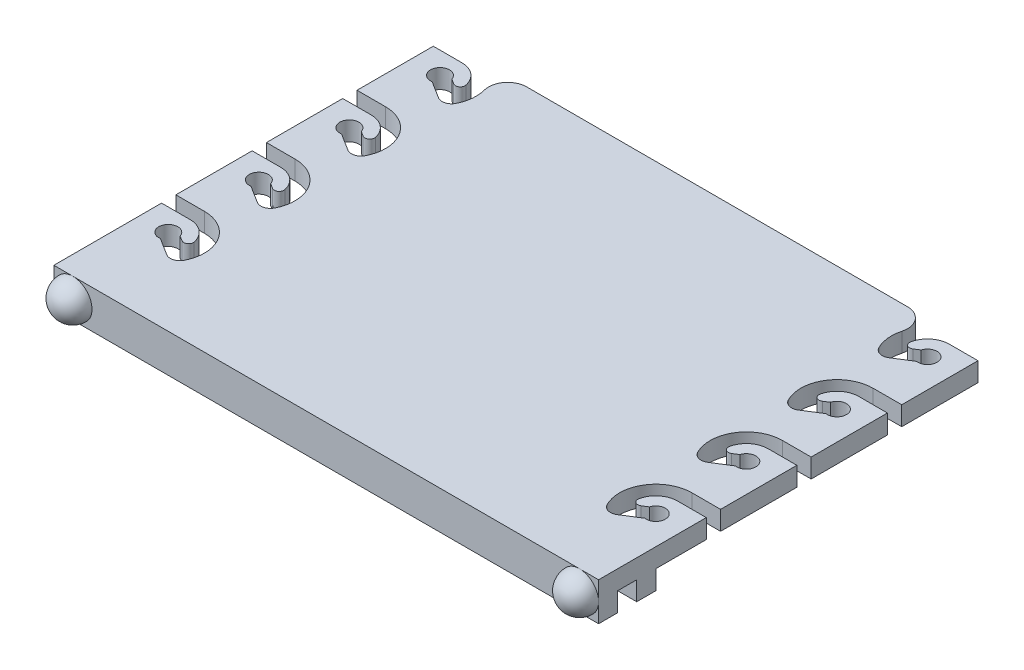
SolidWorks part; units mm, degrees
ref_plane "Front Plane" through (0, 0, 0) normal (0, 0, 1) x (1, 0, 0)
ref_plane "Top Plane" through (0, 0, 0) normal (0, 1, 0) x (1, 0, 0)
ref_plane "Right Plane" through (0, 0, 0) normal (1, 0, 0) x (0, 0, -1)
sketch "Sketch1" plane through (0, 0, 0) normal (0, 1, 0) x (1, 0, 0)
  line L0 (-28.5657, 0) -> (-28.5657, 41)
  line L1 (-28.5657, 0) -> (28.5657, 0)
  line L2 (0, 0) -> (0, 41) construction
  line L3 (-28.5657, 2) -> (-28.5657, 4) construction
  line L4 (28.5657, 0) -> (28.5657, 41)
  line L6 (-28.5657, 41) -> (28.5657, 41)
  line L7 (1.5, 41) -> (-1.5, 41) construction
extrude "Boss-Extrude1" add sketch "Sketch1" along normal blind 2
sketch "Sketch2" plane through (0, 0, 0) normal (0, -1, 0) x (1, 0, 0)
  line L0 (-28.5657, 0) -> (28.5657, 0) construction
  line L1 (-28.5657, 0) -> (28.5657, 0)
  line L2 (-28.5657, -2) -> (28.5657, -2)
  line L3 (28.5657, -2) -> (28.5657, -4)
  line L4 (28.5657, -4) -> (1.5, -4)
  line L5 (1.5, -4) -> (1.5, -20)
  line L8 (-28.5657, -2) -> (-28.5657, -4)
  line L9 (-28.5657, -4) -> (-1.5, -4)
  line L10 (-1.5, -4) -> (-1.5, -20)
  line L12 (0, -41) -> (0, 0) construction
  line L13 (-1.5, -20) -> (-3.5, -20)
  line L14 (-3.5, -20) -> (-3.5, -6)
  line L15 (-3.5, -6) -> (-28.5657, -6)
  line L16 (-28.5657, -6) -> (-28.5657, -4)
  line L17 (28.5657, -6) -> (28.5657, -4)
  line L18 (3.5, -6) -> (28.5657, -6)
  line L19 (1.5, -20) -> (3.5, -20)
  line L20 (3.5, -20) -> (3.5, -6)
  line L21 (-28.5657, -2) -> (-28.5657, 0)
  line L22 (-28.5657, 0) -> (28.5657, 0)
  line L23 (28.5657, 0) -> (28.5657, -2)
  dimension "D1" = 2
  dimension "D2" = 2
  dimension "D3" = 16
extrude "Boss-Extrude2" add sketch "Sketch2" along normal blind 2 contours L2 L12 L22 L21 | L12 L2 L23 L1 | L19 L20 L18 L17 L4 L5 | L16 L15 L14 L13 L10 L9
sketch "Sketch4" plane through (0, 0, 0) normal (0, -1, 0) x (1, 0, 0)
  line L0 (28.5657, 0) -> (-28.5657, 0) construction
  line L1 (-26.5657, 0) -> (-28.5657, 0)
  line L2 (-26.5657, 0) -> (-26.5657, 2)
  line L3 (-26.5657, 0) -> (-26.5657, 6.8868) construction
  arc A0 (-28.5657, 0) -> (-26.5657, 2) centre (-26.5657, 0) cw
  dimension "D1" = 2
revolve "Revolve1" add sketch "Sketch4" angle 360 about L3
mirror "Mirror1" about plane through (0, 0, 0) normal (1, 0, 0) of "Revolve1"
sketch "Sketch7" plane through (0, 2, 0) normal (0, 1, 0) x (1, 0, 0)
  line L0 (0, 0) -> (0, 42.7082) construction
  line L2 (-28.5657, 41) -> (-28.5657, 0) construction
  line L3 (-25.5657, 9) -> (-22.6426, 7.1616) construction
  line L4 (-24.0762, 8.9492) -> (-24.6065, 9.2827)
  line L5 (-24.1292, 7.2105) -> (-25.4051, 8.013)
  line L6 (-28.5657, 11.2947) -> (-25.5657, 11.2947)
  line L7 (-28.5657, 12.7947) -> (-28.5657, 11.2947)
  line L8 (-25.5657, 12.7947) -> (-28.5657, 12.7947)
  line L9 (-24.1292, 7.2105) -> (-23.6087, 6.8832)
  line L10 (-26.5657, 0) -> (26.5657, 0) construction
  arc A0 (-24.6065, 9.2827) -> (-25.4051, 8.013) centre (-25.5657, 9) ccw
  arc A1 (-24.0762, 8.9492) -> (-23.3209, 9.4763) centre (-23.8101, 9.3725) ccw
  arc A2 (-22.1856, 7.2752) -> (-25.5657, 12.7947) centre (-25.5657, 9) ccw
  arc A3 (-23.3209, 9.4763) -> (-25.5657, 11.2947) centre (-25.5657, 9) ccw
  arc A4 (-23.6087, 6.8832) -> (-22.1856, 7.2752) centre (-23.0763, 7.7297) ccw
  point P20 (-23.3306, 8.4803)
  dimension "D1" = 2
  dimension "D6" = 0.5
  dimension "D7" = 1
  dimension "D2" = 9
  dimension "D3" = 3
  dimension "D4" = 1.5
  dimension "D5" = 1.5
extrude "Cut-Extrude4" cut sketch "Sketch7" against normal blind 2
pattern_linear "LPattern1" count 4 spacing 9.5 along (0, 0, -1) of "Cut-Extrude4"
mirror "Mirror2" about plane through (0, 0, 0) normal (1, 0, 0) of "LPattern1", "Cut-Extrude4"
fillet "Fillet1" radius 1 2 edges at (-1.5, -1, -4) (1.5, -1, -4)
fillet "Fillet2" radius 2 2 edges at (-24.0994, 1, -41) (24.0994, 1, -41)
